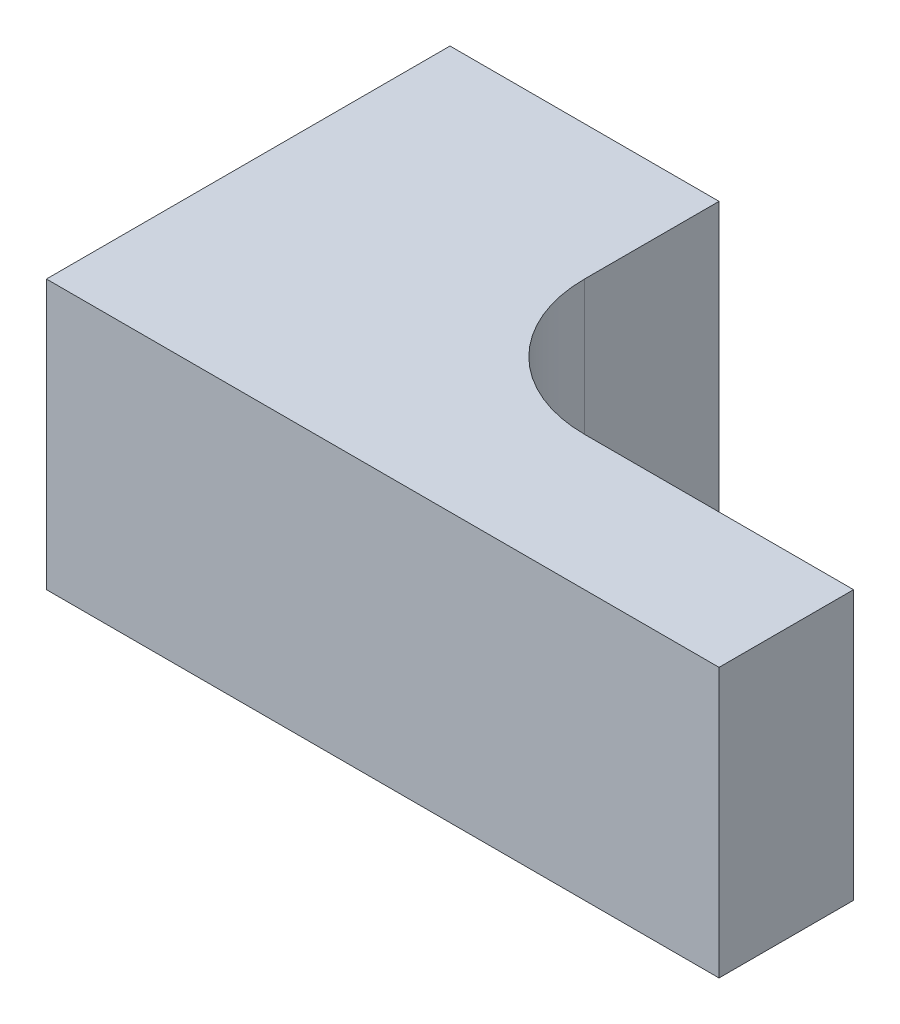
SolidWorks part; units mm, degrees
ref_plane "Přední rovina" through (0, 0, 0) normal (0, 0, 1) x (1, 0, 0)
ref_plane "Horní rovina" through (0, 0, 0) normal (0, 1, 0) x (1, 0, 0)
ref_plane "Pravá rovina" through (0, 0, 0) normal (1, 0, 0) x (0, 0, -1)
sketch "Sketch2" plane through (0, 0, 0) normal (0, 1, 0) x (1, 0, 0)
  line L0 (0, 0) -> (0, -10)
  line L1 (10, -20) -> (30, -20)
  line L2 (30, -20) -> (30, -30)
  line L3 (30, -30) -> (-20, -30)
  line L4 (-20, -30) -> (-20, 0)
  line L5 (-20, 0) -> (0, 0)
  arc A0 (0, -10) -> (10, -20) centre (10, -10) ccw
  dimension "D2" = 10
  dimension "D1" = 20
  dimension "D3" = 20
  dimension "D4" = 10
  dimension "D5" = 10
extrude "Boss-Extrude1" add sketch "Sketch2" along normal blind 20
equation "\"R\"= 10"
equation "\"D2@Sketch2\"=\"R\""
equation "\"D1@Sketch2\"=\"R\" *2"
equation "\"D3@Sketch2\"=\"R\" * 2"
equation "\"D5@Sketch2\"=\"R\""
equation "\"D4@Sketch2\"=\"R\""
